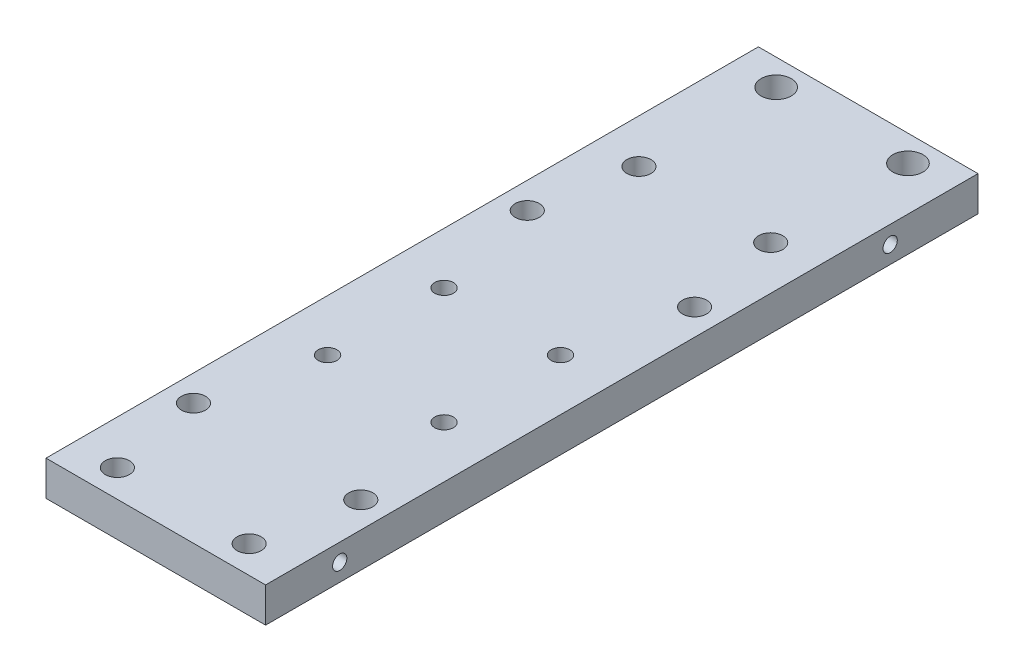
SolidWorks part; units mm, degrees
material "6061 Alloy"
ref_plane "Front Plane" through (0, 0, 0) normal (0, 0, 1) x (1, 0, 0)
ref_plane "Top Plane" through (0, 0, 0) normal (0, 1, 0) x (1, 0, 0)
ref_plane "Right Plane" through (0, 0, 0) normal (1, 0, 0) x (0, 0, -1)
sketch "Sketch1" plane through (0, 0, 0) normal (0, 1, 0) x (1, 0, 0)
  line L1 (-20, 80) -> (20, 80)
  line L2 (-20, 80) -> (-20, -80)
  line L3 (-20, -80) -> (20, -80)
  line L4 (20, 80) -> (20, -80)
  line L5 (0, -80) -> (0, 80) construction
  line L6 (-20, 0) -> (20, 0) construction
  point P0 (0, 0)
  dimension "D1" = 40
  dimension "D2" = 160
extrude "Boss-Extrude1" add sketch "Sketch1" along normal mid plane 6.35
sketch "Sketch3" plane through (0, 0, 0) normal (0, 1, 0) x (1, 0, 0)
  line L0 (0, 75.2375) -> (12, 75.2375) construction
  line L5 (0, -80) -> (0, 80) construction
  line L6 (-20, 0) -> (20, 0) construction
  line L7 (0, 50.2375) -> (12, 50.2375) construction
  line L8 (20, 80) -> (-20, 80) construction
  line L9 (-20, 80) -> (-20, -80) construction
  line L10 (-20, -80) -> (20, -80) construction
  line L11 (20, -80) -> (20, 80) construction
  circle A0 centre (12, 75.2375) radius 2.75
  circle A1 centre (12, 50.2375) radius 2.2
  circle A2 centre (-12, 50.2375) radius 2.2
  circle A3 centre (-12, 75.2375) radius 2.75
  circle A4 centre (-12, -44.7625) radius 2.2
  circle A5 centre (12, -44.7625) radius 2.2
  point P0 (0, 0)
  dimension "D4" = 5.5
  dimension "D5" = 4.4
  dimension "D1" = 4.7625
  dimension "D2" = 25
  dimension "D3" = 12
  dimension "D6" = 2
extrude "M4/5_through" cut sketch "Sketch3" against normal up to surface (3.175 mm away) and the other way blind 6.35 up to face at (0, -3.175, 0)
sketch "Sketch4" plane through (0, 0, -80) normal (0, 0, -1) x (-1, 0, 0)
  circle A0 centre (0, 0) radius 1.3
  dimension "D1" = 2.6
extrude "M3_DRILL" cut sketch "Sketch4" against normal blind 8
sketch "Sketch5" plane through (0, 3.175, 0) normal (0, 1, 0) x (1, 0, 0)
  line L0 (-12, -44.7625) -> (0, -44.7625) construction
  line L2 (0, 0) -> (0, -23.6676) construction
  line L3 (-12, 50.2375) -> (-12, -44.7625) construction
  line L4 (-12, 2.7375) -> (-1.1233, 2.7375) construction
  line L5 (-20, 80) -> (-20, -80) construction
  circle A0 centre (-15.2375, -27.6625) radius 2.2
  circle A1 centre (15.2375, -27.6625) radius 2.2
  circle A2 centre (15.2375, 33.1375) radius 2.2
  circle A3 centre (-15.2375, 33.1375) radius 2.2
  circle A4 centre (-12, -44.7625) radius 2.2 construction
  dimension "D2" = 4.4
  dimension "D1" = 17.1
  dimension "D3" = 4.7625
extrude "M4_through" cut sketch "Sketch5" against normal up to surface (6.35 mm away) up to face at (12, -3.175, 46.9625)
sketch "Sketch6" plane through (0, 0, 0) normal (0, 1, 0) x (1, 0, 0)
  line L0 (0, 2.7375) -> (0, 0) construction
  line L1 (-10.6066, 13.3441) -> (0, 2.7375) construction
  line L2 (-15.2375, 33.1375) -> (-15.2375, -27.6625) construction
  line L3 (-15.2375, 2.7375) -> (0, 2.7375) construction
  circle A0 centre (0, 2.7375) radius 15 construction
  circle A1 centre (-10.6066, 13.3441) radius 1.7
  circle A2 centre (10.6066, 13.3441) radius 1.7
  circle A3 centre (10.6066, -7.8691) radius 1.7
  circle A4 centre (-10.6066, -7.8691) radius 1.7
  point P15 (0, 2.7375)
  dimension "D2" = 30
  dimension "D4" = 3.4
  dimension "D3" = 135
  dimension "D5" = 4
extrude "M4_Drill" cut sketch "Sketch6" along normal up to surface (3.175 mm away) and the other way blind 10 up to face at (-15.2375, 3.175, -35.3375)
sketch "Sketch7" plane through (0, 3.175, 0) normal (0, 1, 0) x (1, 0, 0)
  line L0 (-12, -44.7625) -> (12, -44.7625) construction
  line L1 (20, -80) -> (20, 80) construction
  line L2 (-20, -80) -> (20, -80)
  line L3 (-20, -80) -> (-20, -49.7625)
  line L4 (-20, -49.7625) -> (20, -49.7625)
  line L5 (20, -80) -> (20, -49.7625)
  line L6 (0, -49.7625) -> (0, -80) construction
  line L7 (-20, -64.8812) -> (20, -64.8812) construction
  point P216 (0, -64.8812)
  dimension "D1" = 5
extrude "Cut-Extrude2" cut sketch "Sketch7" against normal up to surface (6.35 mm away) up to face at (-10.6066, -3.175, 9.5691)
sketch "Sketch8" plane through (-20, 0, 0) normal (-1, 0, 0) x (0, 0, 1)
  line L0 (36.2625, -3.175) -> (36.2625, 3.175) construction
  line L4 (-64, -3.175) -> (-64, 3.175) construction
  line L6 (-80, 3.175) -> (49.7625, 3.175) construction
  line L7 (-80, -3.175) -> (49.7625, -3.175) construction
  line L8 (-80, 3.175) -> (-80, -3.175) construction
  line L9 (49.7625, -3.175) -> (49.7625, 3.175) construction
  circle A0 centre (36.2625, 0) radius 1.3
  circle A1 centre (-64, 0) radius 1.3
  point P4 (-75.2576, 3.175)
  point P7 (-69.4942, -3.175)
  point P14 (18.7693, 3.175)
  point P15 (18.7693, -3.175)
  dimension "D2" = 2.6
  dimension "D3" = 2.6
  dimension "D1" = 16
  dimension "D4" = 13.5
extrude "Cut-Extrude3" cut sketch "Sketch8" against normal blind 8
mirror "Mirror1" about plane through (0, 0, 0) normal (1, 0, 0) of "Cut-Extrude3"
